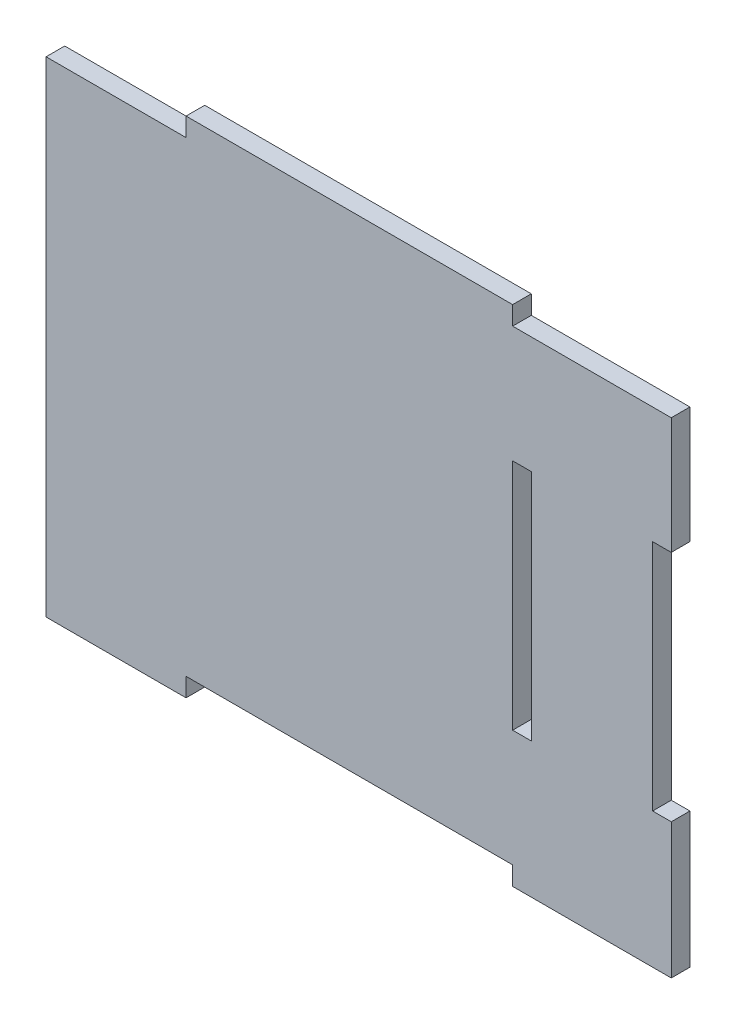
SolidWorks part; units mm, degrees
ref_plane "Спереди" through (0, 0, 0) normal (0, 0, 1) x (1, 0, 0)
ref_plane "Сверху" through (0, 0, 0) normal (0, 1, 0) x (1, 0, 0)
ref_plane "Справа" through (0, 0, 0) normal (1, 0, 0) x (0, 0, -1)
sketch "Эскиз1" plane through (0, 0, 0) normal (0, 0, 1) x (1, 0, 0)
  line L0 (-100, 77.2084) -> (-130, 77.2084)
  line L1 (-30, -22.7916) -> (-100, -22.7916)
  line L2 (0, 2.2084) -> (0, 52.2084)
  line L3 (0, 77.2084) -> (-30, 77.2084)
  line L4 (-130, -22.7916) -> (-130, 77.2084)
  line L6 (-130, -22.7916) -> (-130, -26.7916)
  line L7 (-130, -26.7916) -> (-100, -26.7916)
  line L8 (-100, -22.7916) -> (-100, -26.7916)
  line L11 (0, -26.7916) -> (-30, -26.7916)
  line L12 (-30, -22.7916) -> (-30, -26.7916)
  line L14 (-100, 77.2084) -> (-100, 81.2084)
  line L15 (-100, 81.2084) -> (-30, 81.2084)
  line L16 (-30, 77.2084) -> (-30, 81.2084)
  line L17 (-30, 52.2084) -> (-26, 52.2084)
  line L18 (-30, 52.2084) -> (-30, 2.2084)
  line L19 (-30, 2.2084) -> (-26, 2.2084)
  line L20 (-26, 52.2084) -> (-26, 2.2084)
  line L21 (0, 77.2084) -> (4, 77.2084)
  line L23 (0, 52.2084) -> (4, 52.2084)
  line L24 (4, 77.2084) -> (4, 52.2084)
  line L25 (0, 2.2084) -> (4, 2.2084)
  line L27 (0, -26.7916) -> (4, -26.7916)
  line L28 (4, 2.2084) -> (4, -26.7916)
  dimension "D1" = 100
  dimension "D2" = 4
  dimension "D3" = 30
  dimension "D4" = 4
  dimension "D5" = 50
  dimension "D6" = 26
  dimension "D7" = 25
  dimension "D8" = 30
  dimension "D9" = 70
extrude "Бобышка-Вытянуть1" add sketch "Эскиз1" along normal blind 4
